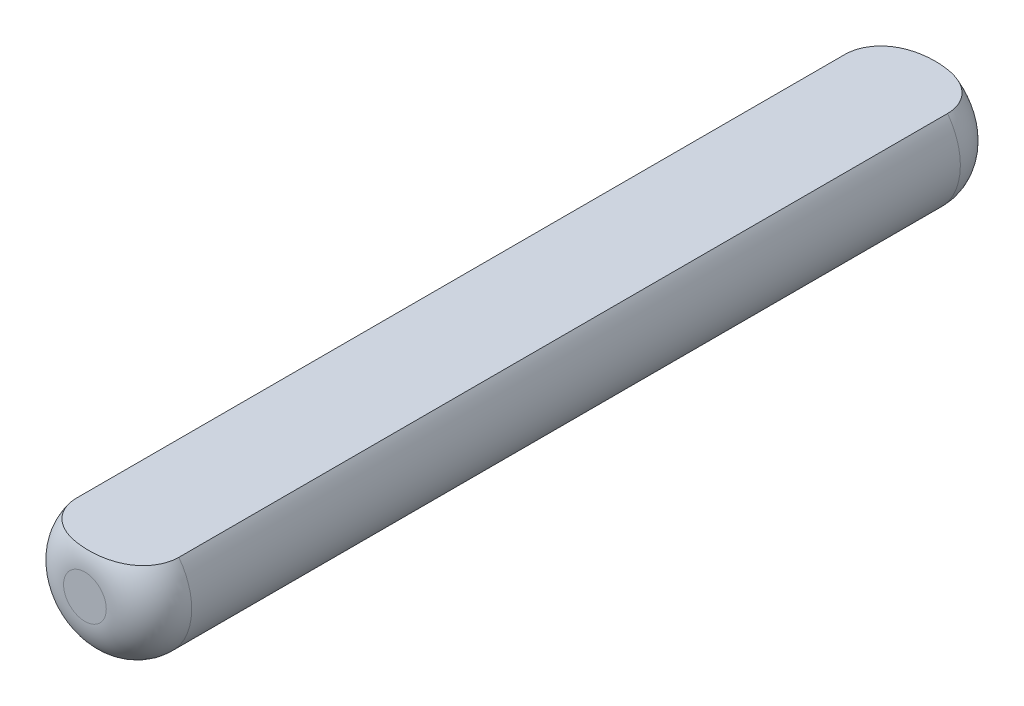
SolidWorks part; units mm, degrees
ref_plane "Plan de face" through (0, 0, 0) normal (0, 0, 1) x (1, 0, 0)
ref_plane "Plan de dessus" through (0, 0, 0) normal (0, 1, 0) x (1, 0, 0)
ref_plane "Plan de droite" through (0, 0, 0) normal (1, 0, 0) x (0, 0, -1)
sketch "Esquisse1" plane through (0, 0, 0) normal (0, 0, 1) x (1, 0, 0)
  circle A0 centre (0, 0) radius 3
  dimension "D1" = 6
extrude "Boss.-Extru.1" add sketch "Esquisse1" along normal blind 40
fillet "Congé1" radius 2 2 edges at (3, 0, 0) (3, 0, 40)
sketch "Esquisse2" plane through (0, 0, 40) normal (0, 0, 1) x (1, 0, 0)
  line L1 (-3, 3) -> (3, 3)
  line L2 (-3, 3) -> (-3, 1.8)
  line L3 (-3, 1.8) -> (3, 1.8)
  line L4 (3, 3) -> (3, 1.8)
  circle A0 centre (0, 0) radius 3 construction
  point P6 (0, 3)
  dimension "D1" = 6
  dimension "D2" = 1.2
extrude "Enlèv. mat.-Extru.1" cut sketch "Esquisse2" against normal through all
sketch "Esquisse3" plane through (0, 0, 0) normal (0, 0, -1) x (-1, 0, 0)
  point P0 (0, 0)
